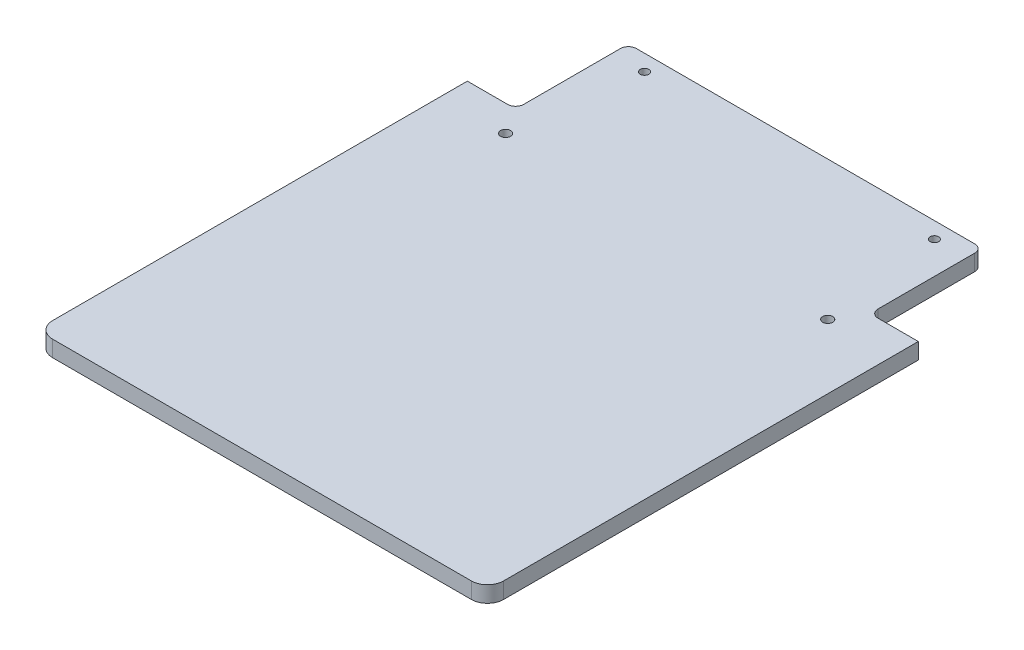
SolidWorks part; units mm, degrees
material "PE High Density"
ref_plane "Front Plane" through (0, 0, 0) normal (0, 0, 1) x (1, 0, 0)
ref_plane "Top Plane" through (0, 0, 0) normal (0, 1, 0) x (1, 0, 0)
ref_plane "Right Plane" through (0, 0, 0) normal (1, 0, 0) x (0, 0, -1)
sketch "Sketch1" plane through (0, 0, 0) normal (0, 1, 0) x (1, 0, 0)
  line L1 (0, 0) -> (355.6, 0)
  line L2 (0, 0) -> (0, 428.625)
  line L3 (0, 428.625) -> (355.6, 428.625)
  line L4 (355.6, 0) -> (355.6, 428.625)
  dimension "D1" = 355.6
  dimension "D2" = 428.625
extrude "Boss-Extrude1" add sketch "Sketch1" along normal blind 12.7
fillet "Fillet1" radius 12.7 2 edges at (355.6, 6.35, 0) (0, 6.35, 0)
sketch "Sketch3" plane through (0, 12.7, 0) normal (0, 1, 0) x (1, 0, 0)
  line L0 (0, 428.625) -> (0, 339.725)
  line L1 (0, 428.625) -> (38.1, 428.625)
  line L2 (0, 339.725) -> (38.1, 339.725)
  line L3 (38.1, 428.625) -> (38.1, 339.725)
  line L4 (0, 428.625) -> (0, 12.7) construction
  line L5 (355.6, 428.625) -> (355.6, 339.725)
  line L6 (355.6, 428.625) -> (317.5, 428.625)
  line L7 (355.6, 339.725) -> (317.5, 339.725)
  line L8 (317.5, 428.625) -> (317.5, 339.725)
  line L9 (355.6, 12.7) -> (355.6, 428.625) construction
  dimension "D1" = 38.1
  dimension "D2" = 88.9
extrude "Cut-Extrude2" cut sketch "Sketch3" against normal through all
fillet "Fillet2" radius 6.35 4 edges at (317.5, 6.35, -339.725) (38.1, 6.35, -339.725) (317.5, 6.35, -428.625) (38.1, 6.35, -428.625)
hole_wizard "H (0.266) Diameter Hole1" positions "Sketch4" profile "Sketch5" hole size "H" standard "ANSI Inch" end condition through all
sketch "Sketch4" plane through (0, 12.7, 0) normal (0, 1, 0) x (1, 0, 0)
  line L0 (311.15, 428.625) -> (44.45, 428.625) construction
  line L1 (317.5, 422.275) -> (317.5, 346.075) construction
  line L2 (38.1, 346.075) -> (38.1, 422.275) construction
  point P0 (63.5, 415.925)
  point P2 (292.1, 415.925)
  dimension "D1" = 12.7
  dimension "D2" = 25.4
  dimension "D3" = 25.4
sketch "Sketch5" plane through (63.5, 12.7, -415.925) normal (1, 0, 0) x (0, 0, 1)
  line L0 (0, 0) -> (0, 12.7)
  line L1 (0, 12.7) -> (3.3782, 12.7)
  line L2 (3.3782, 12.7) -> (3.3782, 0)
  line L5 (3.3782, 0) -> (0, 0)
  line L11 (0, -6.35) -> (0, 107.95) construction
  dimension "Thru Hole Dia." = 6.7564
  dimension "Thru Hole Depth" = 12.7
hole_wizard "5/16 (0.3125) Diameter Hole1" positions "Sketch6" profile "Sketch7" hole size "5/16" standard "ANSI Inch" end condition through all
sketch "Sketch6" plane through (0, 0, 0) normal (0, -1, 0) x (-1, 0, 0)
  line L0 (-38.1, 346.075) -> (-38.1, 422.275) construction
  line L1 (-317.5, 422.275) -> (-317.5, 346.075) construction
  line L2 (-311.15, 428.625) -> (-44.45, 428.625) construction
  point P0 (-50.8, 319.0875)
  point P2 (-304.8, 319.0875)
  dimension "D1" = 12.7
  dimension "D2" = 12.7
  dimension "D3" = 109.5375
sketch "Sketch7" plane through (50.8, 0, -319.0875) normal (1, 0, 0) x (0, 0, -1)
  line L0 (0, 0) -> (0, 12.7)
  line L1 (0, 12.7) -> (3.9687, 12.7)
  line L2 (3.9687, 12.7) -> (3.9687, 0)
  line L5 (3.9687, 0) -> (0, 0)
  line L11 (0, -6.35) -> (0, 107.95) construction
  dimension "Thru Hole Dia." = 7.9375
  dimension "Thru Hole Depth" = 12.7
hole_wizard "CSK for 1/4 Flat Head Machine Screw1" positions "Sketch8" profile "Sketch9" countersink size "1/4" standard "ANSI Inch"
sketch "Sketch8" plane through (0, 12.7, 0) normal (0, 1, 0) x (1, 0, 0)
  line L0 (355.6, 12.7) -> (355.6, 339.725) construction
  line L1 (0, 339.725) -> (0, 12.7) construction
  line L2 (12.7, 0) -> (342.9, 0) construction
  point P0 (63.5, 95.25)
  point P2 (292.1, 95.25)
  dimension "D1" = 63.5
  dimension "D2" = 63.5
  dimension "D3" = 95.25
sketch "Sketch9" plane through (63.5, 12.7, -95.25) normal (1, 0, 0) x (0, 0, 1)
  line L0 (0, 0) -> (0, 12.7)
  line L1 (0, 12.7) -> (3.3782, 12.7)
  line L2 (3.3782, 12.7) -> (3.3782, 3.5209)
  line L3 (3.3782, 3.5209) -> (6.4389, 0)
  line L5 (6.4389, 0) -> (0, 0)
  line L6 (-3.3782, 3.5209) -> (-6.4389, 0) construction
  line L11 (0, -6.35) -> (0, 107.95) construction
  dimension "Thru Hole Dia." = 6.7564
  dimension "Thru Hole Depth" = 12.7
  dimension "Near C'Sink Dia." = 12.8778
  dimension "Near C'Sink Angle" = 82
